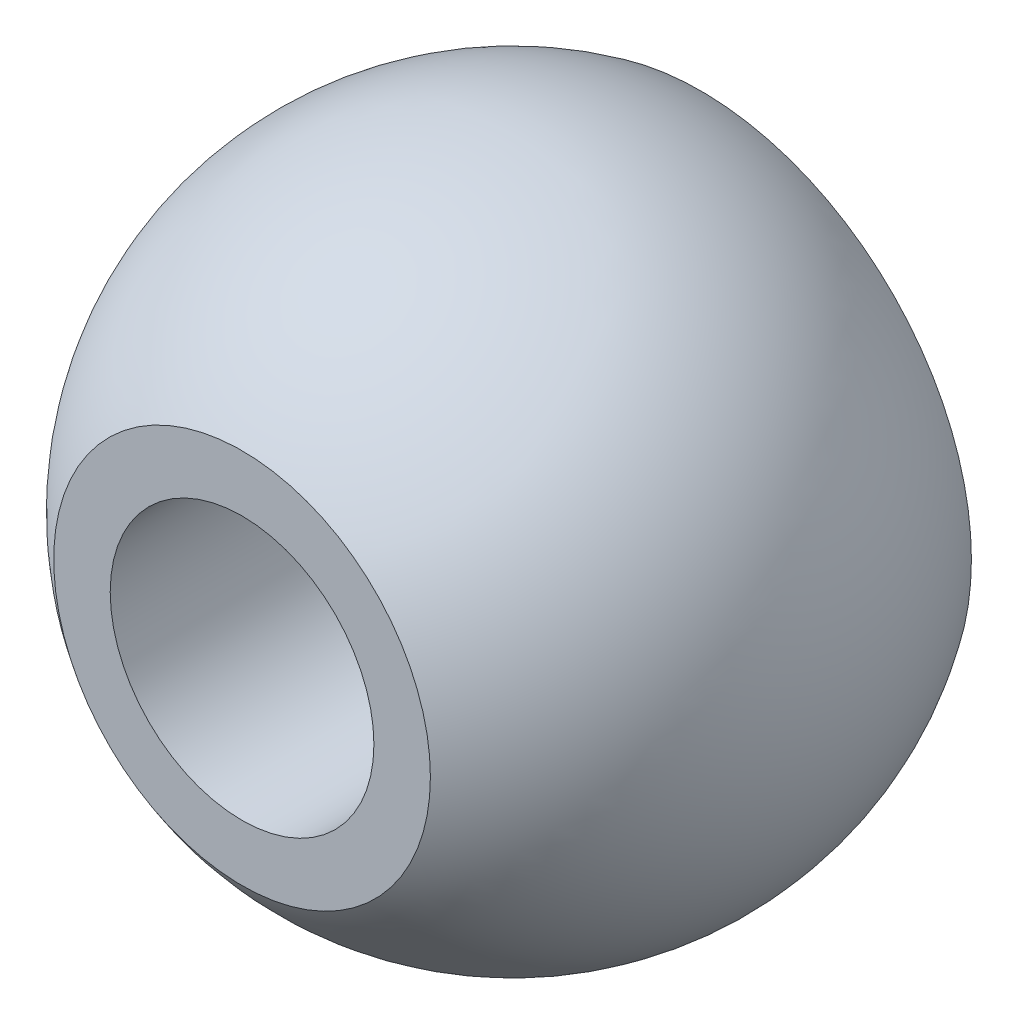
SolidWorks part; units mm, degrees
ref_plane "Front Plane" through (0, 0, 0) normal (0, 0, 1) x (1, 0, 0)
ref_plane "Top Plane" through (0, 0, 0) normal (0, 1, 0) x (1, 0, 0)
ref_plane "Right Plane" through (0, 0, 0) normal (1, 0, 0) x (0, 0, -1)
sketch "Sketch4" plane through (0, 0, 0) normal (0, 1, 0) x (1, 0, 0)
  line L0 (12.3084, 0) -> (10.1, 0)
  line L1 (10.1, 0) -> (10.1, -7.3084)
  line L2 (10.1, -7.3084) -> (11, -7.3084)
  line L3 (8, 0) -> (8, -7.3084) construction
  arc A0 (11, -7.3084) -> (12.3084, 0) centre (8, -3) ccw
revolve "Revolve2" add sketch "Sketch4" angle 360 about L3
